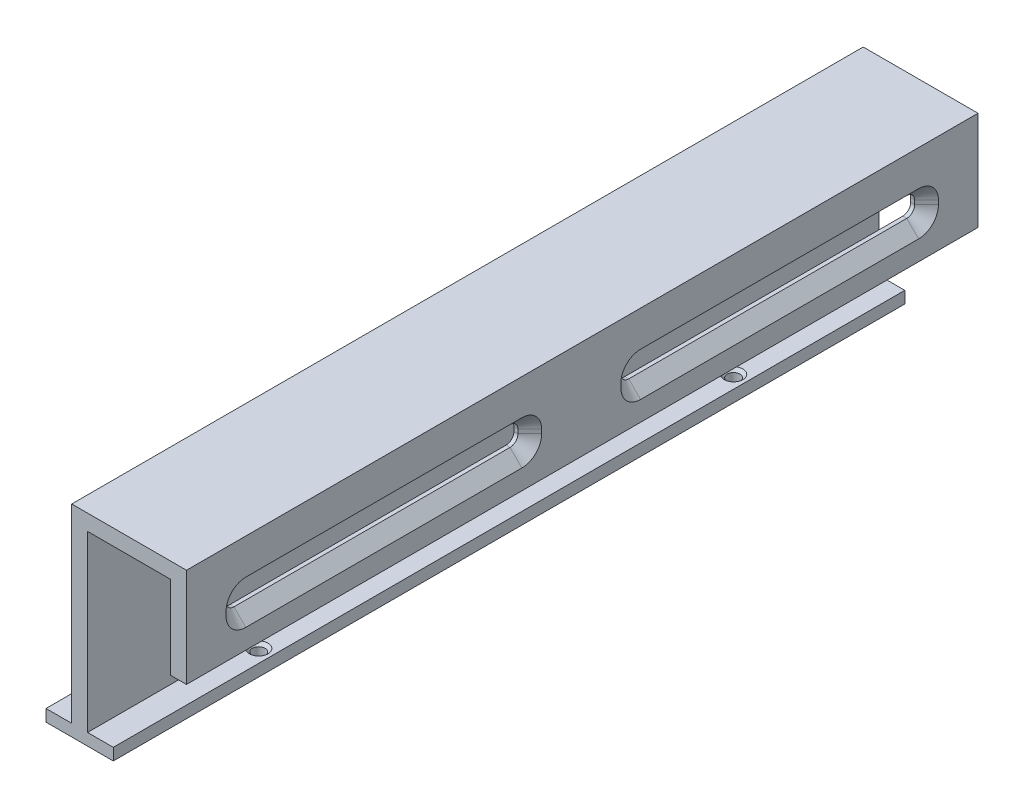
SolidWorks part; units mm, degrees
ref_plane "Front Plane" through (0, 0, 0) normal (0, 0, 1) x (1, 0, 0)
ref_plane "Top Plane" through (0, 0, 0) normal (0, 1, 0) x (1, 0, 0)
ref_plane "Right Plane" through (0, 0, 0) normal (1, 0, 0) x (0, 0, -1)
sketch "Sketch1" plane through (0, 0, 0) normal (0, 0, 1) x (1, 0, 0)
  line L0 (0, 0) -> (0, 48)
  line L5 (0, 48) -> (29, 48)
  line L6 (29, 48) -> (29, 23)
  line L7 (29, 23) -> (25, 23)
  line L8 (25, 23) -> (25, 44)
  line L9 (25, 44) -> (4, 44)
  line L10 (4, 44) -> (4, 0)
  line L12 (10.5, 0) -> (10.5, -3)
  line L13 (10.5, -3) -> (-6.5, -3)
  line L14 (-6.5, -3) -> (-6.5, 0)
  line L16 (0, 0) -> (-6.5, 0)
  line L17 (4, 0) -> (10.5, 0)
  dimension "D1" = 4
  dimension "D2" = 4
  dimension "D3" = 4
  dimension "D4" = 21
  dimension "D5" = 21
  dimension "D6" = 6.5
  dimension "D7" = 3
  dimension "D8" = 6.5
  dimension "D9" = 23
extrude "Boss-Extrude1" add sketch "Sketch1" against normal blind 200
sketch "Sketch2" plane through (29, 0, 0) normal (1, 0, 0) x (0, 0, -1)
  line L0 (99.75, 48) -> (99.75, 23) construction
  line L1 (200, 48) -> (0, 48) construction
  line L2 (200, 23) -> (0, 23) construction
  line L3 (200, 23) -> (200, 48) construction
  line L4 (0, 33.5) -> (200, 33.5) construction
  line L5 (0, 23) -> (0, 48) construction
  line L7 (15, 36) -> (84.75, 36)
  line L8 (13, 34) -> (13, 33)
  line L9 (15, 31) -> (84.75, 31)
  line L10 (86.75, 34) -> (86.75, 33)
  line L11 (114.75, 36) -> (185, 36)
  line L12 (112.75, 34) -> (112.75, 33)
  line L13 (114.75, 31) -> (185, 31)
  line L14 (187, 34) -> (187, 33)
  arc A8 (185, 31) -> (187, 33) centre (185, 33) ccw
  arc A9 (185, 36) -> (187, 34) centre (185, 34) cw
  arc A10 (112.75, 33) -> (114.75, 31) centre (114.75, 33) ccw
  arc A11 (114.75, 36) -> (112.75, 34) centre (114.75, 34) ccw
  arc A12 (84.75, 31) -> (86.75, 33) centre (84.75, 33) ccw
  arc A13 (84.75, 36) -> (86.75, 34) centre (84.75, 34) cw
  arc A14 (13, 33) -> (15, 31) centre (15, 33) ccw
  arc A15 (15, 36) -> (13, 34) centre (15, 34) ccw
  point P20 (13, 33.5)
  point P21 (112.75, 33.5)
  dimension "D2" = 99.75
  dimension "D3" = 15
  dimension "D4" = 2
  dimension "D5" = 10.5
  dimension "D9" = 15
  dimension "D11" = 15
  dimension "D12" = 15
  dimension "D13" = 5
extrude "Cut-Extrude1" cut sketch "Sketch2" against normal up to surface (4 mm away) up to face at (25, 33.5, -100)
chamfer "Chamfer1" distance 3 angle 45 16 edges at (29, 36, -149.875) (29, 35.4142, -113.3358) (29, 35.4142, -186.4142) (29, 33.5, -112.75) (29, 33.5, -187) (29, 31.5858, -113.3358) (29, 31.5858, -186.4142) (29, 31, -149.875) (29, 36, -49.875) (29, 35.4142, -13.5858) (29, 35.4142, -86.1642) (29, 33.5, -13) (29, 33.5, -86.75) (29, 31.5858, -13.5858) (29, 31.5858, -86.1642) (29, 31, -49.875)
sketch "Sketch3" plane through (0, -3, 0) normal (0, -1, 0) x (1, 0, 0)
  line L0 (2, 0) -> (2, -200) construction
  line L1 (-6.5, 0) -> (10.5, 0) construction
  line L2 (-6.5, -200) -> (10.5, -200) construction
  line L3 (-6.5, -100) -> (10.5, -100) construction
  line L4 (-6.5, -200) -> (-6.5, 0) construction
  line L5 (10.5, -200) -> (10.5, 0) construction
  circle A0 centre (-3.25, -40) radius 1.6
  circle A7 centre (-3.25, -160) radius 1.6
  circle A8 centre (7.25, -160) radius 1.6
  circle A9 centre (7.25, -40) radius 1.6
  point P2 (0, 0)
  point P15 (-3.25, -91.0932)
  point P16 (0, 0)
  dimension "D1" = 3.2
  dimension "D3" = 60
  dimension "D2" = 3.25
extrude "Cut-Extrude2" cut sketch "Sketch3" against normal up to surface (3 mm away) up to face at (-3.25, 0, -100)
chamfer "Chamfer2" distance 0.75 angle 45 4 edges at (-4.85, 0, -40) (5.65, 0, -160) (5.65, 0, -40) (-4.85, 0, -160)
